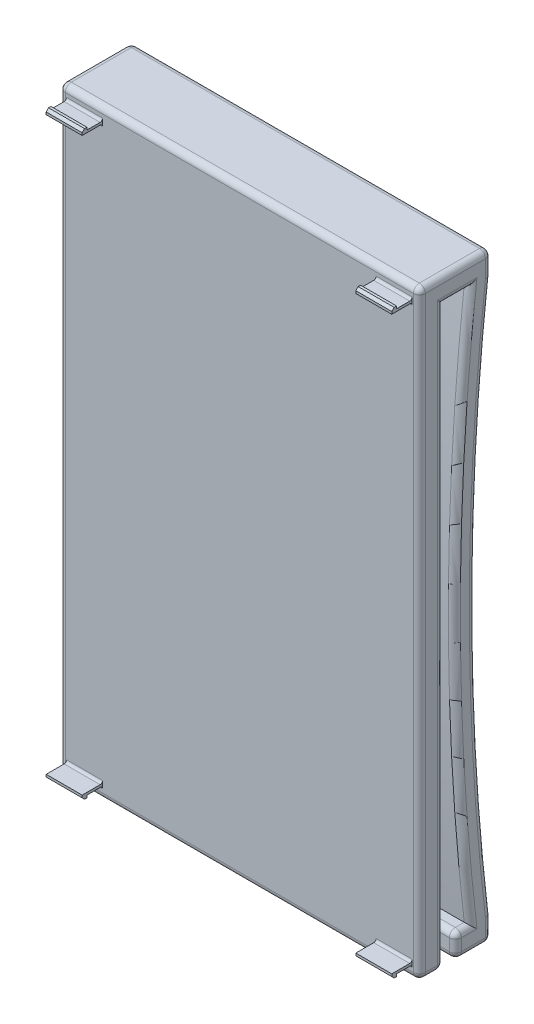
SolidWorks part; units mm, degrees
material "ABS"
ref_plane "Front Plane" through (0, 0, 0) normal (0, 0, 1) x (1, 0, 0)
ref_plane "Top Plane" through (0, 0, 0) normal (0, 1, 0) x (1, 0, 0)
ref_plane "Right Plane" through (0, 0, 0) normal (1, 0, 0) x (0, 0, -1)
sketch "Sketch1" plane through (0, 0, 0) normal (1, 0, 0) x (0, 0, -1)
  line L0 (0, 0) -> (0, 50)
  line L1 (0, 50) -> (6, 50)
  line L2 (0, 0) -> (2, 0)
  line L3 (2, 0) -> (2, 48)
  line L4 (2, 48) -> (4.2382, 48)
  line L10 (6, 50) -> (6, 48)
  line L11 (4.2382, 2) -> (3, 2)
  line L12 (3, 2) -> (3, 0)
  line L13 (3, 0) -> (6, 0)
  line L14 (6, 0) -> (6, 2)
  arc A3 (6, 48) -> (6, 2) centre (202.9113, 25) ccw
  arc A4 (4.2382, 48) -> (4.2382, 2) centre (202.9113, 25) ccw
  dimension "D1" = 50
  dimension "D2" = 1.75
  dimension "D3" = 2
  dimension "D5" = 2
  dimension "D6" = 200
  dimension "D4" = 2
  dimension "D7" = 3
  dimension "D8" = 6
extrude "Clip Body" add sketch "Sketch1" along normal mid plane 30
sketch "Sketch9" plane through (-15, 0, 0) normal (-1, 0, 0) x (0, 0, 1)
  line L7 (0, 50) -> (0, 0) construction
  line L8 (1.7, 48.8) -> (1.7, 49)
  line L9 (0, 49) -> (0, 48.8)
  line L10 (0, 48.8) -> (1.7, 48.8)
  line L11 (1.7, 49) -> (1.5, 49.2)
  line L12 (1.5, 49.2) -> (1.3, 49.2)
  line L13 (1.3, 49.2) -> (1.3, 49)
  line L14 (1.3, 49) -> (0, 49)
  line L15 (-6, 50) -> (0, 50) construction
  line L16 (0, 25) -> (8.2378, 25) construction
  line L17 (0, 50) -> (0, 0) construction
  line L18 (1.3, 1) -> (0, 1)
  line L19 (1.3, 0.8) -> (1.3, 1)
  line L20 (1.5, 0.8) -> (1.3, 0.8)
  line L21 (1.7, 1) -> (1.5, 0.8)
  line L22 (0, 1.2) -> (1.7, 1.2)
  line L23 (0, 1) -> (0, 1.2)
  line L24 (1.7, 1.2) -> (1.7, 1)
  dimension "D2" = 1
  dimension "D3" = 0.2
  dimension "D7" = 0.2
  dimension "D8" = 0.4
  dimension "D9" = 0.2
  dimension "D10" = 1.3
  dimension "D11" = 135
extrude "Prism Cantilever Extrude" add sketch "Sketch9" against normal blind 3 from offset 0.6 offset against normal yes
fillet "Prism Cantilever Extrude Fillet" radius 0.2 4 edges at (-12.9, 1, 0) (-12.9, 1.2, 0) (-12.9, 48.8, 0) (-12.9, 49, 0)
mirror "Prism Cantilever Extrude Mirror" about plane through (0, 0, 0) normal (1, 0, 0) of "Prism Cantilever Extrude Fillet", "Prism Cantilever Extrude"
fillet "Global Fillet" radius 0.5 33 edges at (-15, 0, -1) (15, 0, -1) (0, 0, 0) (0, 50, 0) (15, 25, 0) (-15, 25, 0) (-15, 50, -3) (15, 50, -3) (15, 49, -6) (-15, 49, -6) (0, 48, -6) (-15, 25, -4.6613) (15, 25, -4.6613) (15, 1, -6) (-15, 1, -6) (0, 2, -6) (0, 0, -6) (-15, 0, -4.5) (15, 0, -4.5) (15, 1, -3) (15, 2, -3.6191) (0, 0, -3) (0, 0, -2) (-15, 1, -3) (0, 2, -3) (-15, 2, -3.6191) (-15, 24, -2) (-15, 48, -3.1191) (-15, 25, -2.9113) (15, 25, -2.9113) (15, 48, -3.1191) (15, 24, -2) (0, 50, -6)
